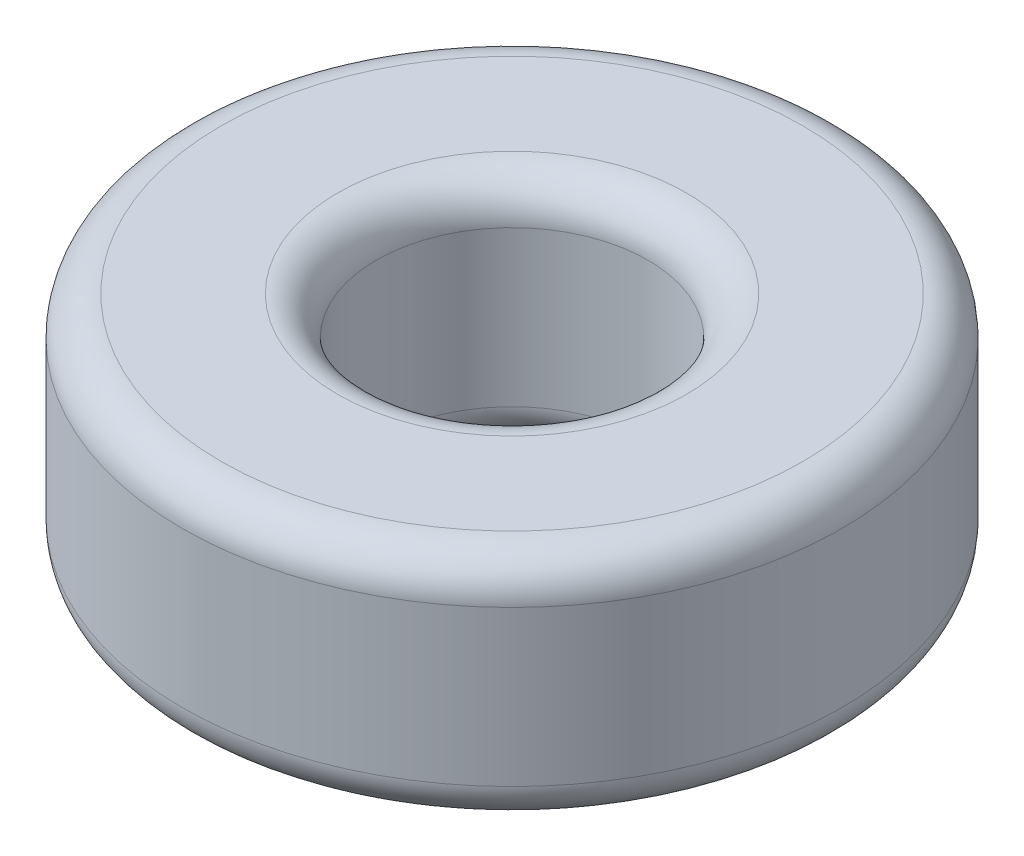
SolidWorks part; units mm, degrees
material "AISI 1020 鋼，冷軋"
ref_plane "Front Plane" through (0, 0, 0) normal (0, 0, 1) x (1, 0, 0)
ref_plane "Top Plane" through (0, 0, 0) normal (0, 1, 0) x (1, 0, 0)
ref_plane "Right Plane" through (0, 0, 0) normal (1, 0, 0) x (0, 0, -1)
sketch "草圖1" plane through (0, 0, 0) normal (0, 1, 0) x (1, 0, 0)
  circle A0 centre (0, 0) radius 3.5
  circle A1 centre (0, 0) radius 8.5
  dimension "D1" = 7
  dimension "D2" = 17
extrude "填料-伸長1" add sketch "草圖1" along normal blind 6
fillet "圓角1" radius 1 3 edges at (0, 0, 3.5) (0, 6, 3.5) (0, 6, 8.5)
fillet "圓角2" radius 1 1 edges at (0, 0, 8.5)
